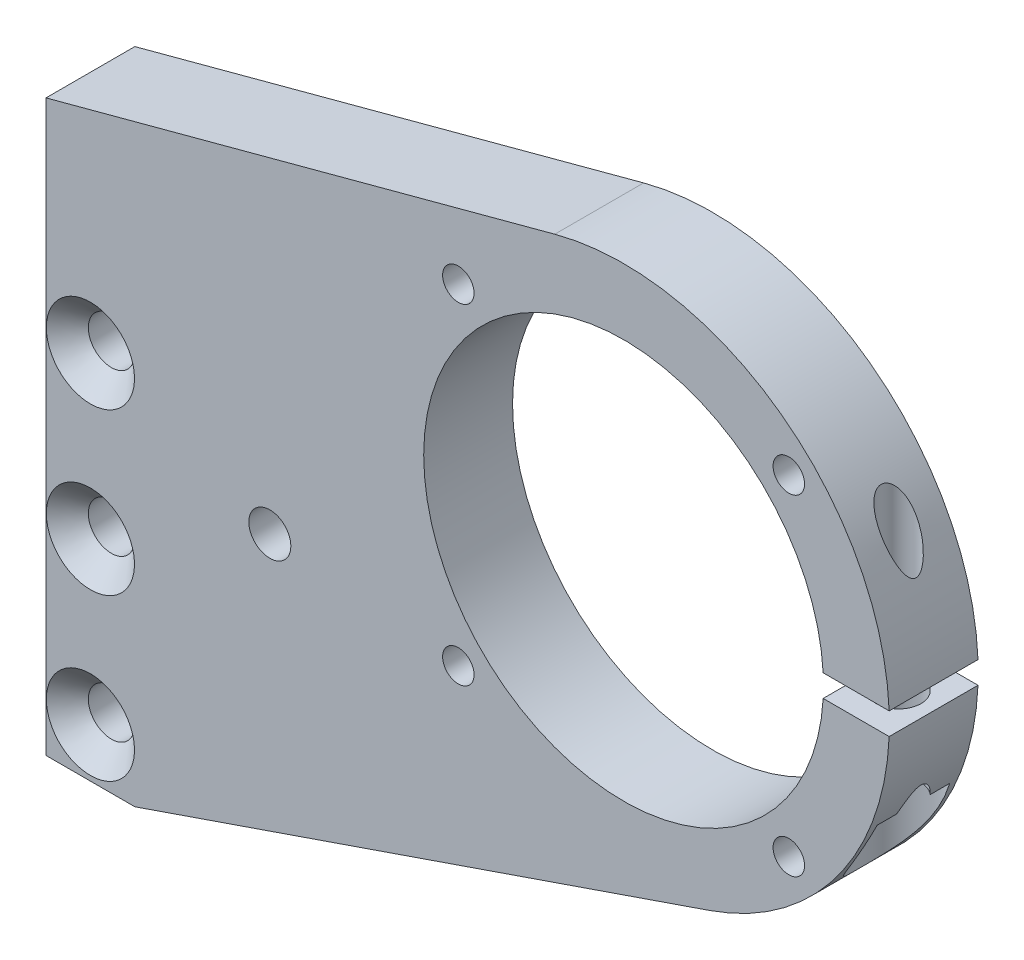
SolidWorks part; units mm, degrees
ref_plane "Front Plane" through (0, 0, 0) normal (0, 0, 1) x (1, 0, 0)
ref_plane "Top Plane" through (0, 0, 0) normal (0, 1, 0) x (1, 0, 0)
ref_plane "Right Plane" through (0, 0, 0) normal (1, 0, 0) x (0, 0, -1)
ref_plane "Plane1" through (0, 0, 0) normal (0, 0, -1) x (-1, 0, 0)
sketch "Sketch1" plane through (0, 0, 0) normal (0, 0, -1) x (-1, 0, 0)
  line L0 (224.1695, 127.7225) -> (151.4352, 147.2116)
  line L1 (129.2465, 74.5705) -> (211.4695, 46.305)
  line L2 (211.4695, 46.305) -> (224.1695, 46.305)
  line L3 (224.1695, 46.305) -> (224.1695, 127.7225)
  arc A0 (151.4352, 147.2116) -> (129.2465, 74.5705) centre (141.6001, 110.5064) ccw
extrude "Boss-Extrude1" add sketch "Sketch1" against normal blind 12.7
sketch "Sketch2" plane through (0, 0, 12.7) normal (0, 0, 1) x (1, 0, 0)
  line L0 (-103.6333, 112.0939) -> (-113.179, 112.0939)
  line L1 (-113.179, 108.9189) -> (-103.6333, 108.9189)
  arc A0 (-103.6333, 108.9189) -> (-103.6333, 112.0939) centre (-141.6001, 110.5064) ccw
  arc A1 (-113.179, 112.0939) -> (-113.179, 108.9189) centre (-141.6001, 110.5064) cw
extrude "Cut-Extrude1" cut sketch "Sketch2" against normal through all
ref_plane "Plane2" through (0, 110.5064, 0) normal (0, 1, 0) x (1, 0, 0)
sketch "Sketch3" plane through (0, 110.5064, 0) normal (0, 1, 0) x (1, 0, 0)
  line L0 (-113.0251, 0) -> (-141.6001, 0)
  line L1 (-141.6001, 0) -> (-141.6001, -12.7)
  line L2 (-141.6001, -12.7) -> (-113.0251, -12.7)
  line L3 (-113.0251, -12.7) -> (-113.0251, 0)
  line L4 (-141.6001, 0) -> (-141.6001, -12.7) construction
  dimension "D1" = 28.575
revolve "Cut-Revolve1" cut sketch "Sketch3" angle 360 about L4
hole_wizard "#8 Clearance Hole1" positions "Sketch5" profile "Sketch4" hole size "#8" standard "ANSI Inch"
sketch "Sketch5" plane through (0, 0, 12.7) normal (0, 0, 1) x (1, 0, 0)
  line L0 (-141.6001, 139.0814) -> (-141.6001, 81.9314) construction
  arc A0 (-113.0692, 112.0939) -> (-113.0692, 108.9189) centre (-141.6001, 110.5064) ccw construction
  point P0 (-117.9781, 86.8844)
  point P1 (-165.2221, 86.8844)
  point P2 (-165.2221, 134.1284)
  point P3 (-117.9781, 134.1284)
  point P12 (-141.6001, 110.5064)
  dimension "D1" = 47.244
  dimension "D2" = 47.244
  dimension "D3" = 23.622
  dimension "D4" = 47.244
  dimension "D5" = 23.622
  dimension "D6" = 23.622
  dimension "D7" = 47.244
  dimension "D8" = 23.622
sketch "Sketch4" plane through (-117.9781, 86.8844, 12.7) normal (1, 0, 0) x (0, -1, 0)
  line L0 (0, 0) -> (0, 12.7)
  line L1 (0, 12.7) -> (2.25, 12.7)
  line L2 (2.25, 12.7) -> (2.25, 0)
  line L5 (2.25, 0) -> (0, 0)
  line L11 (0, -6.35) -> (0, 107.95) construction
  dimension "Thru Hole Dia." = 4.5
  dimension "Thru Hole Depth" = 12.7
hole_wizard "1/4 Clearance Hole1" positions "Sketch7" profile "Sketch6" hole size "1/4" standard "ANSI Inch"
sketch "Sketch7" plane through (0, 0, 0) normal (0, 0, -1) x (-1, 0, 0)
  point P0 (217.8195, 53.305)
  point P1 (217.8195, 76.305)
  point P2 (217.8195, 99.305)
sketch "Sketch6" plane through (-217.8195, 53.305, 0) normal (1, 0, 0) x (0, 1, 0)
  line L0 (0, 0) -> (0, 12.7)
  line L1 (0, 12.7) -> (3.3, 12.7)
  line L2 (3.3, 12.7) -> (3.3, 0)
  line L5 (3.3, 0) -> (0, 0)
  line L11 (0, -6.35) -> (0, 107.95) construction
  dimension "Thru Hole Dia." = 6.6
  dimension "Thru Hole Depth" = 12.7
hole_wizard "#12 Clearance Hole1" positions "Sketch9" profile "Sketch8" hole size "#12" standard "ANSI Inch"
sketch "Sketch9" plane through (0, 0, 12.7) normal (0, 0, 1) x (1, 0, 0)
  point P0 (-192.1695, 89.7225)
sketch "Sketch8" plane through (-192.1695, 89.7225, 12.7) normal (1, 0, 0) x (0, -1, 0)
  line L0 (0, 0) -> (0, 12.7)
  line L1 (0, 12.7) -> (3, 12.7)
  line L2 (3, 12.7) -> (3, 0)
  line L5 (3, 0) -> (0, 0)
  line L11 (0, -6.35) -> (0, 107.95) construction
  dimension "Thru Hole Dia." = 6
  dimension "Thru Hole Depth" = 12.7
ref_plane "Plane3" through (0, 84.1425, 0) normal (0, -1, 0) x (-1, 0, 0)
hole_wizard "Hole1" positions "Sketch11" profile "Sketch10" legacy
sketch "Sketch11" plane through (0, 84.1425, 0) normal (0, -1, 0) x (-1, 0, 0)
  point P0 (108.6333, -6.35)
sketch "Sketch10" plane through (-108.6333, 84.1425, 6.35) normal (1, 0, 0) x (0, 0, -1)
  line L0 (0, 0) -> (0, 24.7764)
  line L1 (0, 24.7764) -> (3.2, 24.7764)
  line L2 (3.2, 24.7764) -> (3.2, 11.7764)
  line L3 (3.2, 11.7764) -> (5.6, 11.7764)
  line L4 (5.6, 11.7764) -> (5.6, 0)
  line L5 (5.6, 0) -> (0, 0)
  line L6 (0, 110) -> (0, -10) construction
  dimension "Diameter" = 6.4
  dimension "Depth" = 24.7764
  dimension "C-Bore Diameter" = 11.2
  dimension "C-Bore Depth" = 11.7764
hole_wizard "#10 Clearance Hole1" positions "Sketch13" profile "Sketch12" hole size "#10" standard "ANSI Inch"
sketch "Sketch13" plane through (0, 112.0939, 0) normal (0, -1, 0) x (-1, 0, 0)
  point P0 (108.6333, -6.35)
sketch "Sketch12" plane through (-108.6333, 112.0939, 6.35) normal (1, 0, 0) x (0, 0, -1)
  line L0 (0, 0) -> (0, 36.4125)
  line L1 (0, 36.4125) -> (2.5, 36.4125)
  line L2 (2.5, 36.4125) -> (2.5, 0)
  line L5 (2.5, 0) -> (0, 0)
  line L11 (0, -6.35) -> (0, 107.95) construction
  dimension "Thru Hole Dia." = 5
  dimension "Thru Hole Depth" = 36.4125
chamfer "Chamfer1" distance 3 angle 45 3 edges at (-221.1195, 53.305, 0) (-221.1195, 76.305, 0) (-221.1195, 99.305, 0)
sketch "Sketch14" plane through (0, 0, 0) normal (0, 0, -1) x (-1, 0, 0)
  circle A0 centre (192.1695, 89.7225) radius 4
  circle A1 centre (192.1695, 89.7225) radius 3 construction
  circle A2 centre (192.1695, 89.7225) radius 3
  point P0 (192.1695, 89.7225)
  dimension "D1" = 8
extrude "Boss-Extrude2" add sketch "Sketch14" against normal up to surface (12.7 mm away) up to face at (-189.1695, 89.7225, 12.7)
mirror "镜向1" about plane through (-141.6001, 110.5064, 12.7) normal (0, 0, -1) of bodies 111
sketch "草图1" plane through (0, 46.305, 0) normal (0, -1, 0) x (1, 0, 0)
  line L0 (-224.1695, 25.4) -> (-224.1695, 0) construction
  line L1 (-224.1695, 12.7) -> (-88.067, 12.7)
  line L2 (-224.1695, 12.7) -> (-224.1695, -21.9507)
  line L3 (-224.1695, -21.9507) -> (-88.067, -21.9507)
  line L4 (-88.067, 12.7) -> (-88.067, -21.9507)
extrude "切除-拉伸1" cut sketch "草图1" against normal through all
